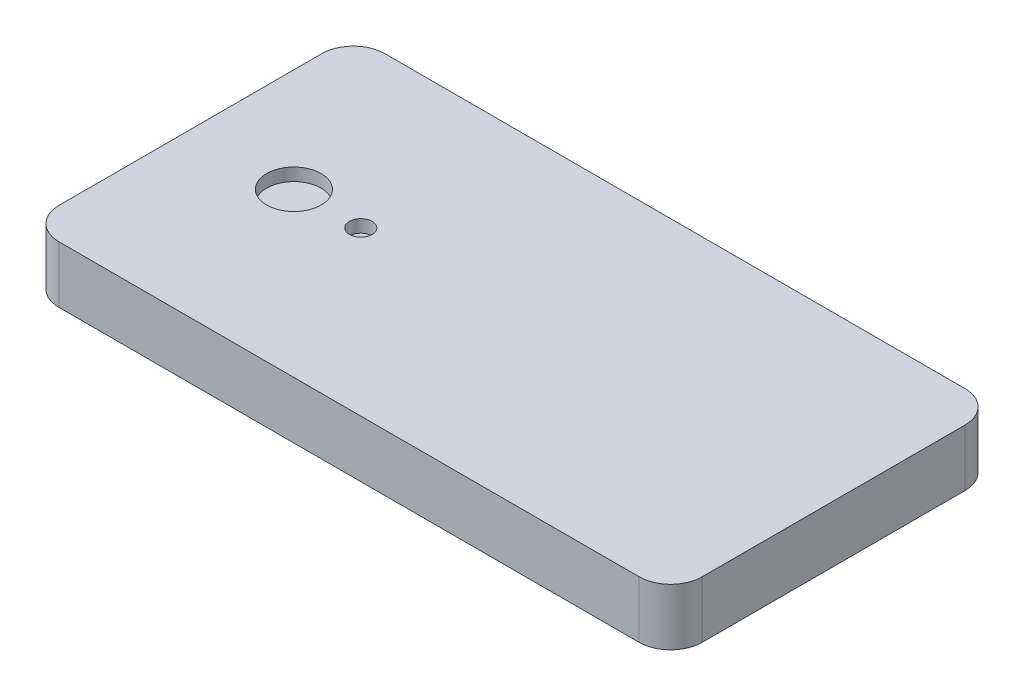
SolidWorks part; units mm, degrees
ref_plane "Front Plane" through (0, 0, 0) normal (0, 0, 1) x (1, 0, 0)
ref_plane "Top Plane" through (0, 0, 0) normal (0, 1, 0) x (1, 0, 0)
ref_plane "Right Plane" through (0, 0, 0) normal (1, 0, 0) x (0, 0, -1)
sketch "Sketch1" plane through (0, 0, 0) normal (0, 1, 0) x (1, 0, 0)
  line L1 (-5.7349, 2.7293) -> (123.7035, 2.7293)
  line L2 (-5.7349, 2.7293) -> (-5.7349, -62.8535)
  line L3 (-5.7349, -62.8535) -> (123.7035, -62.8535)
  line L4 (123.7035, 2.7293) -> (123.7035, -62.8535)
  dimension "D1" = 129.4384
  dimension "D2" = 65.5828
extrude "Boss-Extrude1" add sketch "Sketch1" along normal blind 11.43 contours L1 L4 L3 L2
fillet "Fillet1" radius 6.35 4 edges at (123.7035, 5.715, 62.8535) (123.7035, 5.715, -2.7293) (-5.7349, 5.715, -2.7293) (-5.7349, 5.715, 62.8535)
sketch "Sketch2" plane through (0, 11.43, 0) normal (0, 1, 0) x (1, 0, 0)
  line L0 (15.0931, -30.0621) -> (-5.7349, -30.0621) construction
  line L1 (-5.7349, -3.6207) -> (-5.7349, -56.5035) construction
  line L2 (15.0931, -30.0621) -> (28.5551, -30.0621) construction
  circle A0 centre (15.0931, -30.0621) radius 5.4864
  circle A1 centre (28.5551, -30.0621) radius 2.286
  dimension "D3" = 10.9728
  dimension "D4" = 4.572
  dimension "D1" = 34.29
  dimension "D2" = 20.828
extrude "Cut-Extrude1" cut sketch "Sketch2" against normal blind 2.54
